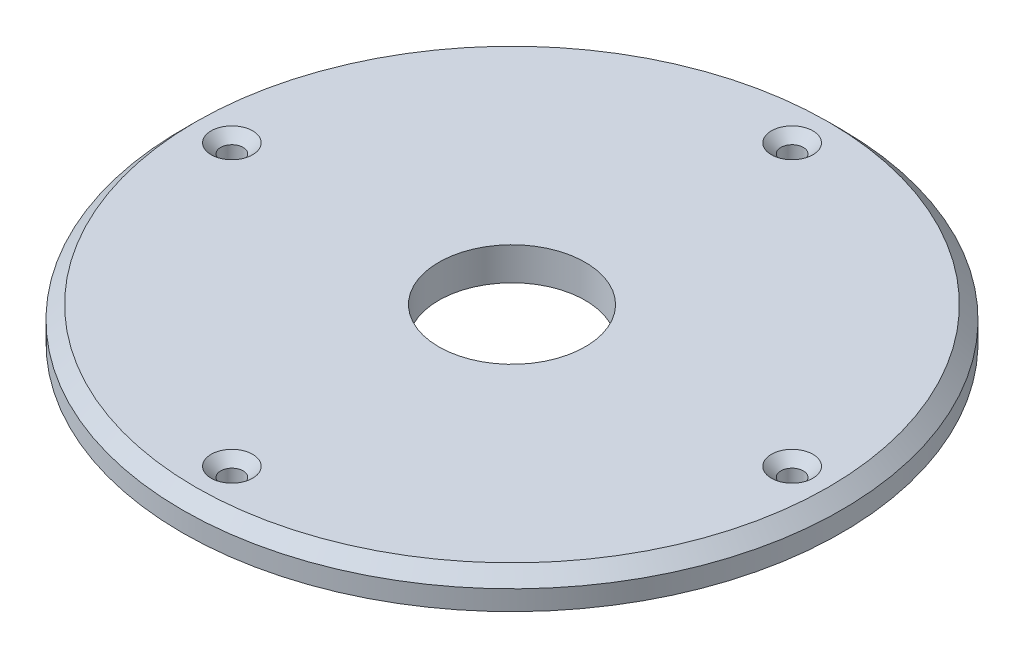
SolidWorks part; units mm, degrees
ref_plane "Front Plane" through (0, 0, 0) normal (0, 0, 1) x (1, 0, 0)
ref_plane "Top Plane" through (0, 0, 0) normal (0, 1, 0) x (1, 0, 0)
ref_plane "Right Plane" through (0, 0, 0) normal (1, 0, 0) x (0, 0, -1)
sketch "Sketch1" plane through (0, 0, 0) normal (0, 1, 0) x (1, 0, 0)
  circle A0 centre (0, 0) radius 50
  circle A1 centre (0, 0) radius 11.1125
  point P0 (0, 42.5)
  point P5 (16.8071, 39.0355)
  point P6 (0, 0)
  dimension "D2" = 22.225
  dimension "D3" = 100
  dimension "D1" = 42.5
extrude "Boss-Extrude1" add sketch "Sketch1" along normal blind 5
sketch "Sketch2" plane through (0, 5, 0) normal (0, 1, 0) x (1, 0, 0)
  point P0 (0, 42.5)
hole_wizard "CSK for M3 Flat Head Machine Screw1" positions "Sketch2" profile "Sketch3" countersink size "M3" standard "ANSI Metric" end condition up to next
sketch "Sketch3" plane through (0, 5, -42.5) normal (1, 0, 0) x (0, 0, 1)
  line L0 (0, 0) -> (0, 5)
  line L1 (0, 5) -> (1.7, 5)
  line L2 (1.7, 5) -> (1.7, 1.45)
  line L3 (1.7, 1.45) -> (3.15, 0)
  line L5 (3.15, 0) -> (0, 0)
  line L6 (-1.7, 1.45) -> (-3.15, 0) construction
  line L11 (0, -6.35) -> (0, 107.95) construction
  dimension "Thru Hole Dia." = 3.4
  dimension "Thru Hole Depth" = 5
  dimension "Near C'Sink Dia." = 6.3
  dimension "Near C'Sink Angle" = 90
pattern_circular "CirPattern1" count 4 every 90 about axis through (0, 0, 0) along (0, 1, 0) of "CSK for M3 Flat Head Machine Screw1"
chamfer "Chamfer1" distance 2 angle 45 1 edges at (0, 5, 50)
